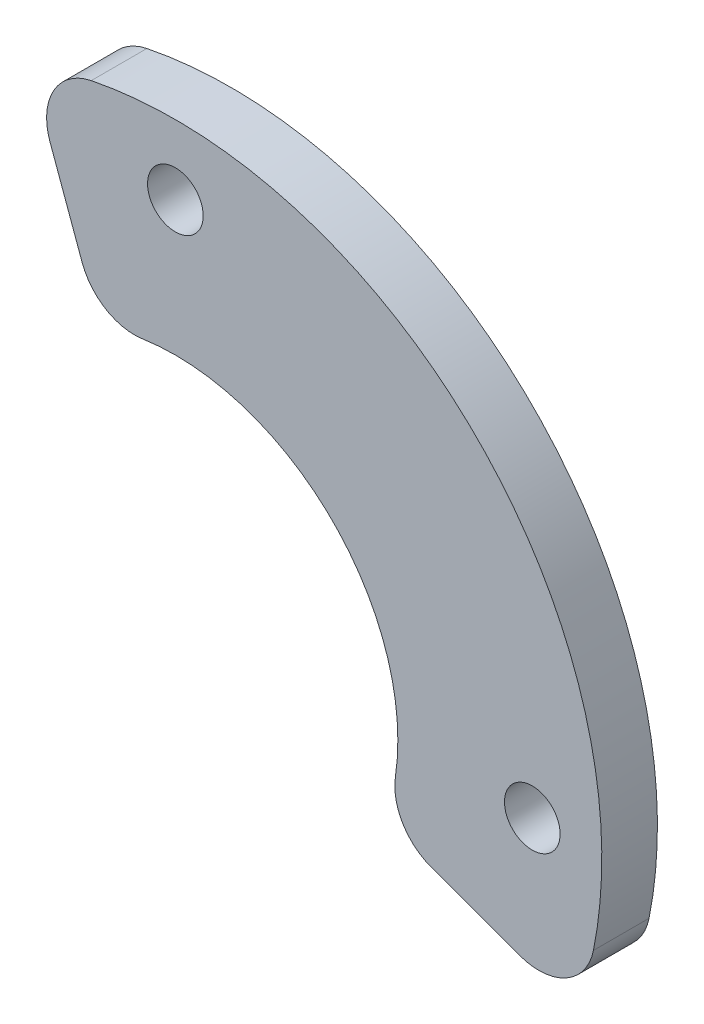
SolidWorks part; units mm, degrees
ref_plane "前视基准面" through (0, 0, 0) normal (0, 0, 1) x (1, 0, 0)
ref_plane "上视基准面" through (0, 0, 0) normal (0, 1, 0) x (1, 0, 0)
ref_plane "右视基准面" through (0, 0, 0) normal (1, 0, 0) x (0, 0, -1)
other "Configuration Table"
sketch "草图1" plane through (0, 0, 0) normal (0, 0, 1) x (1, 0, 0)
  line L0 (0, 0) -> (-7.8665, 21.6129)
  line L1 (0, 0) -> (21.6129, -7.8665)
  line L2 (0, 19.25) -> (0, 0) construction
  line L3 (19.25, 0) -> (0, 0) construction
  circle A0 centre (0, 19.25) radius 1.5
  circle A1 centre (19.25, 0) radius 1.5
  circle A2 centre (0, -19.25) radius 1.5 construction
  circle A3 centre (-19.25, 0) radius 1.5 construction
  circle A4 centre (0, 0) radius 12
  circle A5 centre (0, 0) radius 23
  point P12 (0, 0)
  dimension "D1" = 3
  dimension "D4" = 24
  dimension "D5" = 46
  dimension "D2" = 19.25
  dimension "D6" = 20
  dimension "D7" = 20
  dimension "D3" = 4
extrude "凸台-拉伸1" add sketch "草图1" along normal blind 3 contours L1 A5 L0 A4 A0 A1
fillet "圆角1" radius 3 4 edges at (21.6129, -7.8665, 1.5) (11.2763, -4.1042, 1.5) (-7.8665, 21.6129, 1.5) (-4.1042, 11.2763, 1.5)
